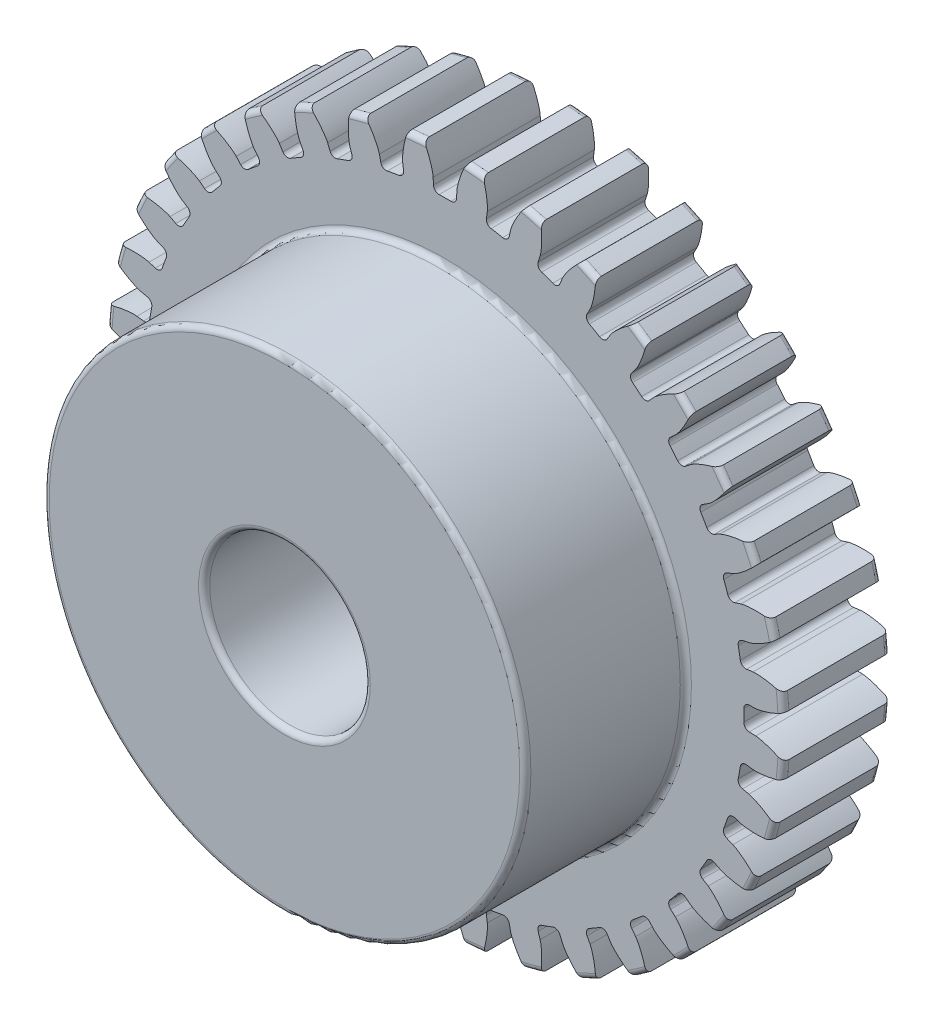
SolidWorks part; units mm, degrees
ref_plane "Front Plane" through (0, 0, 0) normal (0, 0, 1) x (1, 0, 0)
ref_plane "Top Plane" through (0, 0, 0) normal (0, 1, 0) x (1, 0, 0)
ref_plane "Right Plane" through (0, 0, 0) normal (1, 0, 0) x (0, 0, -1)
sketch "Sketch1" plane through (0, 0, 0) normal (0, 0, 1) x (1, 0, 0)
  line L0 (0, 0) -> (0, 19.05) construction
  line L1 (-4.6178, 20.2442) -> (4.6178, 17.8558) construction
  circle A0 centre (0, 0) radius 17.7271 construction
  circle A1 centre (0, 0) radius 20.1083 construction
  circle A2 centre (0, 0) radius 19.05 construction
  circle A3 centre (0, 0) radius 18.4432 construction
  circle A4 centre (0, 0) radius 4.7625 construction
  circle A5 centre (0, 0) radius 14.2875 construction
  circle A6 centre (0, 0) radius 7.9375 construction
  point P8 (304.8, 0)
  point P13 (457.2, 0)
  dimension "OD | Outside Diameter" = 40.2167
  dimension "Root Diameter" = 35.4542
  dimension "Gear Pitch Diameter" = 38.1
  dimension "Base Diameter" = 36.8864
  dimension "Hub Diameter" = 28.575
  dimension "For Shaft Diameter Min" = 9.525
  dimension "For Shaft Diameter Max" = 15.875
  dimension "Pressure Angle" = 14.5
  dimension "Number of Teeth" = 914.4
  dimension "Gear Pitch | Diametral Pitch" = 609.6
sketch "Sketch2" plane through (0, 0, 0) normal (1, 0, 0) x (0, 0, -1)
  line L0 (-7.9375, 0) -> (7.9375, 0) construction
  line L1 (-7.9375, 20.1083) -> (7.9375, 20.1083) construction
  point P2 (0, 20.1083)
  point P4 (1.5875, 20.1083)
  dimension "Overall Width" = 15.875
  dimension "Hub Width" = 9.525
  dimension "Face Width" = 6.35
sketch "Sketch3" plane through (0, 0, 0) normal (0, 0, 1) x (1, 0, 0)
  circle A0 centre (0, 0) radius 20.1083
  circle A1 centre (0, 0) radius 20.1083 construction
extrude "Boss-Extrude1" add sketch "Sketch3" against normal up to vertex (7.9375 mm away) and the other way up to vertex (7.9375 mm away) up to point (0, 0, -7.9375) other way up to point (0, 0, 7.9375)
sketch "Sketch5" plane through (0, 0, 0) normal (1, 0, 0) x (0, 0, -1)
  line L1 (-7.9375, 20.1083) -> (1.5875, 20.1083)
  line L2 (-7.9375, 20.1083) -> (-7.9375, 14.2875)
  line L3 (-7.9375, 14.2875) -> (1.5875, 14.2875)
  line L4 (1.5875, 20.1083) -> (1.5875, 14.2875)
  line L11 (-7.9375, 4.7625) -> (7.9375, 4.7625)
  line L12 (-7.9375, 4.7625) -> (-7.9375, 0)
  line L13 (-7.9375, 0) -> (7.9375, 0)
  line L14 (7.9375, 4.7625) -> (7.9375, 0)
  point P5 (0, 14.2875)
  point P10 (0, 4.7625)
revolve "Cut-Revolve1" cut sketch "Sketch5" angle 360 about L0
fillet "Fillet2" radius 0.3308 6 edges at (20.1083, 0, -7.9375) (4.7625, 0, -7.9375) (4.7625, 0, 7.9375) (14.2875, 0, 7.9375) (14.2875, 0, -1.5875) (20.1083, 0, -1.5875)
sketch "Sketch4" plane through (0, 0, 0) normal (0, 0, 1) x (1, 0, 0)
  line L0 (0, 0) -> (17.7142, 0.675) construction
  line L2 (0, 0) -> (17.7142, -0.675) construction
  line L4 (17.7142, 0.675) -> (18.4298, 0.7023)
  line L5 (18.4298, -0.7023) -> (17.7142, -0.675)
  arc A0 (17.7142, 0.675) -> (17.7142, -0.675) centre (0, 0) cw
  arc A3 (20.0688, 1.2597) -> (20.0688, -1.2597) centre (0, 0) cw
  circle A4 centre (0, 0) radius 20.1083 construction
  spline S0 degree 4 poles (18.4298, 0.7023) (18.4324, 0.7024) (18.4396, 0.7028) (18.4532, 0.7039) (18.4754, 0.7061) (18.5037, 0.7094) (18.5402, 0.7145) (18.5832, 0.7213) (18.6304, 0.7297) (18.6818, 0.7399) (18.733, 0.751) (18.784, 0.7629) (18.8348, 0.7754) (18.8964, 0.7916) (18.9701, 0.8122) (19.0563, 0.838) (19.1539, 0.8695) (19.2533, 0.9039) (19.3511, 0.9396) (19.4499, 0.9779) (19.5453, 1.0164) (19.6444, 1.0587) (19.7359, 1.0989) (19.8383, 1.1464) (19.9209, 1.1855) (20.0297, 1.2396) (20.094, 1.2724) (20.1692, 1.3117) (20.2026, 1.3296) (20.2232, 1.3407) knots 0 0 0 0 0 0.005377 0.015084 0.028532 0.04661 0.064855 0.092111 0.119476 0.146842 0.174209 0.201575 0.228941 0.256307 0.307035 0.361767 0.4165 0.471232 0.525964 0.580697 0.635429 0.690161 0.744894 0.799626 0.854358 0.909091 0.954545 1 1 1 1 1 construction
  spline S1 degree 4 poles (18.4298, 0.7023) (18.4324, 0.7024) (18.4396, 0.7028) (18.4532, 0.7039) (18.4754, 0.7061) (18.5037, 0.7094) (18.5402, 0.7145) (18.5832, 0.7213) (18.6304, 0.7297) (18.6818, 0.7399) (18.733, 0.751) (18.784, 0.7629) (18.8348, 0.7754) (18.8964, 0.7916) (18.9701, 0.8122) (19.0563, 0.838) (19.1539, 0.8695) (19.2533, 0.9039) (19.3511, 0.9396) (19.4499, 0.9779) (19.5453, 1.0164) (19.6444, 1.0587) (19.7359, 1.0989) (19.8383, 1.1464) (19.9209, 1.1855) (20.0061, 1.2279) (20.0476, 1.2488) (20.0688, 1.2597) knots 0 0 0 0 0 0.005377 0.015084 0.028532 0.04661 0.064855 0.092111 0.119476 0.146842 0.174209 0.201575 0.228941 0.256307 0.307035 0.361767 0.4165 0.471232 0.525964 0.580697 0.635429 0.690161 0.744894 0.799626 0.854358 0.909091 0.909091 0.909091 0.909091 0.909091
  spline S2 degree 4 poles (18.4298, -0.7023) (18.4324, -0.7024) (18.4396, -0.7028) (18.4532, -0.7039) (18.4754, -0.7061) (18.5037, -0.7094) (18.5402, -0.7145) (18.5832, -0.7213) (18.6304, -0.7297) (18.6818, -0.7399) (18.733, -0.751) (18.784, -0.7629) (18.8348, -0.7754) (18.8964, -0.7916) (18.9701, -0.8122) (19.0563, -0.838) (19.1539, -0.8695) (19.2533, -0.9039) (19.3511, -0.9396) (19.4499, -0.9779) (19.5453, -1.0164) (19.6444, -1.0587) (19.7359, -1.0989) (19.8383, -1.1464) (19.9209, -1.1855) (20.0297, -1.2396) (20.094, -1.2724) (20.1692, -1.3117) (20.2026, -1.3296) (20.2232, -1.3407) knots 0 0 0 0 0 0.005377 0.015084 0.028532 0.04661 0.064855 0.092111 0.119476 0.146842 0.174209 0.201575 0.228941 0.256307 0.307035 0.361767 0.4165 0.471232 0.525964 0.580697 0.635429 0.690161 0.744894 0.799626 0.854358 0.909091 0.954545 1 1 1 1 1 construction
  spline S3 degree 4 poles (18.4298, -0.7023) (18.4324, -0.7024) (18.4396, -0.7028) (18.4532, -0.7039) (18.4754, -0.7061) (18.5037, -0.7094) (18.5402, -0.7145) (18.5832, -0.7213) (18.6304, -0.7297) (18.6818, -0.7399) (18.733, -0.751) (18.784, -0.7629) (18.8348, -0.7754) (18.8964, -0.7916) (18.9701, -0.8122) (19.0563, -0.838) (19.1539, -0.8695) (19.2533, -0.9039) (19.3511, -0.9396) (19.4499, -0.9779) (19.5453, -1.0164) (19.6444, -1.0587) (19.7359, -1.0989) (19.8383, -1.1464) (19.9209, -1.1855) (20.0061, -1.2279) (20.0476, -1.2488) (20.0688, -1.2597) knots 0 0 0 0 0 0.005377 0.015084 0.028532 0.04661 0.064855 0.092111 0.119476 0.146842 0.174209 0.201575 0.228941 0.256307 0.307035 0.361767 0.4165 0.471232 0.525964 0.580697 0.635429 0.690161 0.744894 0.799626 0.854358 0.909091 0.909091 0.909091 0.909091 0.909091
  dimension "D1" = 35.4542
extrude "Cut-Extrude1" cut sketch "Sketch4" against normal through all both and the other way through all
fillet "Fillet1" radius 0.3308 2 edges at (17.7142, -0.675, -4.7625) (17.7142, 0.675, -4.7625)
pattern_circular "CirPattern1" count 36 over 360 about axis through (0, 0, 7.9375) along (0, 0, -1) of "Cut-Extrude1", "Fillet1"
equation "\"Root Diameter@Sketch1\"=\"Root Diameter\""
equation "\"OD | Outside Diameter@Sketch1\"=\"Outside Diameter\""
equation "\"D1@CirPattern1\"=\"Number of Teeth\""
equation "\"Diametral Pitch\"= 24"
equation "\"Number of Teeth\"=36"
equation "\"Pressure Angle\"=14.5"
equation "\"Pitch Diameter\"= \"Number of Teeth\" / \"Diametral Pitch\""
equation "\"Base Diameter\"= \"Pitch Diameter\" * cos ( \"Pressure Angle\" )"
equation "\"Outside Diameter\"= ( \"Number of Teeth\" + 2 ) / \"Diametral Pitch\""
equation "\"Dedendum\"= 1.25 / \"Diametral Pitch\""
equation "\"Root Diameter\"= \"Pitch Diameter\" - ( 2 * \"Dedendum\" )"
equation "\"Pitch Angle\"= 360deg / \"Number of Teeth\""
equation "\"Alpha\"= sqr ( \"Pitch Diameter\" ^ 2 - \"Base Diameter\" ^ 2 ) / \"Base Diameter\" * 180 / PI - \"Pressure Angle\""
equation "\"Beta\"= ( \"Pitch Angle\" / 4 - \"Alpha\" )"
equation "\"Phi\"= sqr ( ( \"Outside Diameter\" / 2 ) ^ 2 - ( \"Base Diameter\" / 2 ) ^ 2 ) / ( \"Base Diameter\" / 2 )"
equation "\"Addendum\"= 1 / \"Diametral Pitch\""
equation "\"WorkingDepth\"= 2 / \"Diametral Pitch\""
equation "\"WholeDepth\"= 2.25 / \"Diametral Pitch\""
equation "\"Clearance\"= 0.25 / \"Diametral Pitch\""
equation "\"ToothThickness\"= ( pi * 2 ) / \"Diametral Pitch\""
equation "\"CircularPitch\"= pi / \"Diametral Pitch\""
equation "\"Number of Teeth@Sketch1\"=\"Number of Teeth\""
equation "\"Gear Pitch | Diametral Pitch@Sketch1\"=\"Diametral Pitch\""
equation "\"Pressure Angle@Sketch1\"=\"Pressure Angle\""
equation "\"Gear Pitch Diameter@Sketch1\"=\"Pitch Diameter\""
equation "\"Base Diameter@Sketch1\"=\"Base Diameter\""
equation "\"Fillet\"= \"Clearance\" * cos ( \"Pressure Angle\" ) * tan ( ( 90 + \"Pressure Angle\" ) / 2 )"
equation "\"D1@Fillet1\"=\"Fillet\""
equation "\"D1@Sketch4\"=if( \"Base Diameter\">\"Root Diameter\",\"Root Diameter\",\"Base Diameter\"-.00001)"
equation "\"D1@Fillet2\"=\"Fillet\""
